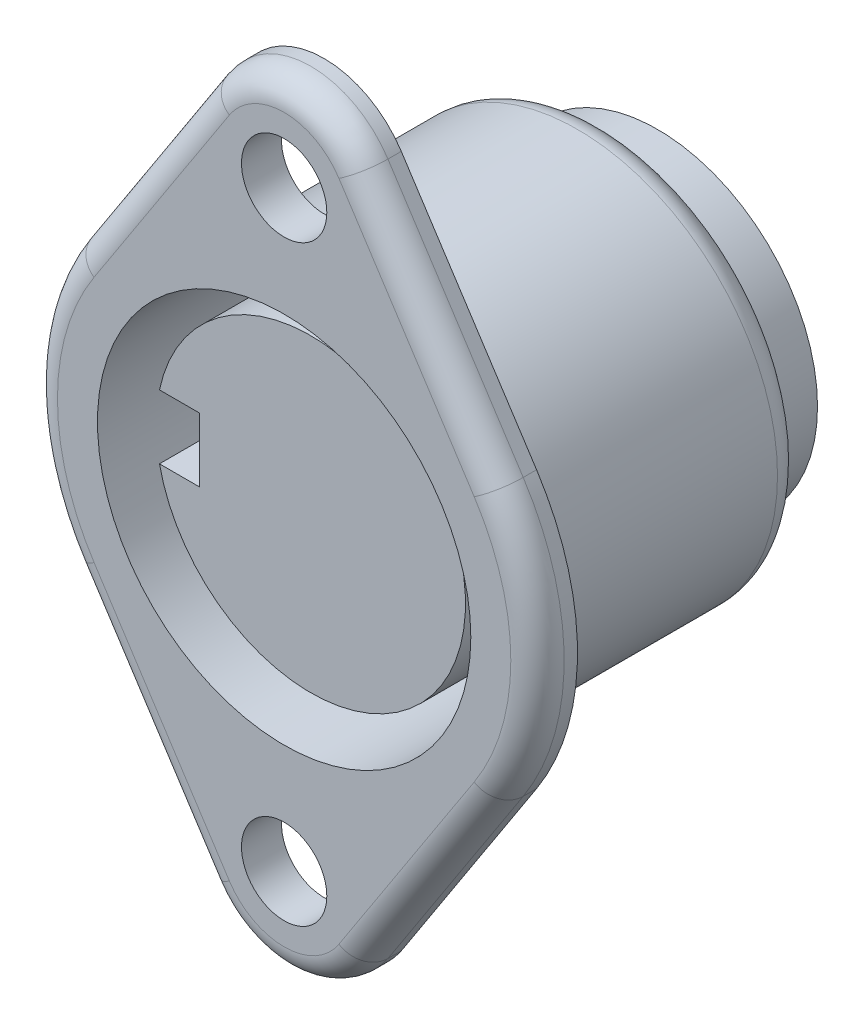
SolidWorks part; units mm, degrees
material "ABS"
ref_plane "Front Plane" through (0, 0, 0) normal (0, 0, 1) x (1, 0, 0)
ref_plane "Top Plane" through (0, 0, 0) normal (0, 1, 0) x (1, 0, 0)
ref_plane "Right Plane" through (0, 0, 0) normal (1, 0, 0) x (0, 0, -1)
sketch "Sketch1" plane through (0, 0, 0) normal (0, 0, 1) x (1, 0, 0)
  circle A0 centre (0, 0) radius 7.5
  dimension "D1" = 15
extrude "Boss-Extrude1" add sketch "Sketch1" along normal blind 10.5
fillet "Fillet1" radius 1 1 edges at (7.5, 0, 0)
sketch "Sketch2" plane through (0, 0, 0) normal (0, 0, -1) x (-1, 0, 0)
  circle A0 centre (0, 0) radius 6
  dimension "D1" = 12
extrude "Boss-Extrude2" add sketch "Sketch2" along normal blind 2
sketch "Sketch3" plane through (0, 0, 10.5) normal (0, 0, 1) x (1, 0, 0)
  line L0 (0, 0) -> (0, 14.55) construction
  line L1 (0, 0) -> (0, -14.55) construction
  line L2 (-9.5, 0) -> (9.5, 0) construction
  line L3 (-7.9649, 5.1779) -> (-2.8925, 12.9804)
  line L4 (7.9649, 5.1779) -> (2.8925, 12.9804)
  line L5 (7.9649, -5.1779) -> (2.8925, -12.9804)
  line L6 (-7.9649, -5.1779) -> (-2.8925, -12.9804)
  circle A0 centre (0, 0) radius 9.5 construction
  circle A1 centre (0, 11.1) radius 3.45 construction
  circle A2 centre (0, -11.1) radius 3.45 construction
  arc A3 (-7.9649, -5.1779) -> (-7.9649, 5.1779) centre (0, 0) cw
  arc A4 (7.9649, -5.1779) -> (7.9649, 5.1779) centre (0, 0) ccw
  arc A5 (-2.8925, -12.9804) -> (2.8925, -12.9804) centre (0, -11.1) ccw
  arc A6 (-2.8925, 12.9804) -> (2.8925, 12.9804) centre (0, 11.1) cw
  circle A7 centre (0, -11.1) radius 1.6
  circle A8 centre (0, 11.1) radius 1.6
  point P7 (0, 11.1)
  point P8 (0, -11.1)
  dimension "D6" = 3.2
  dimension "D1" = 14.55
  dimension "D2" = 29.1
  dimension "D3" = 19
  dimension "D4" = 22.2
  dimension "D5" = 3.45
extrude "Boss-Extrude3" add sketch "Sketch3" along normal blind 1.5
fillet "Fillet2" radius 1 8 edges at (-9.5, 0, 12) (-5.4287, 9.0792, 12) (0, 14.55, 12) (5.4287, 9.0792, 12) (9.5, 0, 12) (5.4287, -9.0792, 12) (0, -14.55, 12) (-5.4287, -9.0792, 12)
sketch "Sketch4" plane through (0, 0, 12) normal (0, 0, 1) x (1, 0, 0)
  circle A0 centre (0, 0) radius 7
  dimension "D1" = 14
extrude "Cut-Extrude1" cut sketch "Sketch4" against normal blind 8.34
sketch "Sketch5" plane through (0, 0, 3.66) normal (0, 0, 1) x (1, 0, 0)
  circle A0 centre (0, 0) radius 5.8
  dimension "D1" = 11.6
extrude "Boss-Extrude4" add sketch "Sketch5" along a picked direction on the side of the normal offset from surface (7.34 mm away) 1
sketch "Sketch6" plane through (0, 0, 11) normal (0, 0, 1) x (1, 0, 0)
  line L0 (0, 0) -> (-8.0806, 0) construction
  line L1 (-5.6745, -1.2) -> (-4.1745, -1.2)
  line L2 (-4.1745, -1.2) -> (-4.1745, 1.2)
  line L3 (-4.1745, 1.2) -> (-5.6745, 1.2)
  circle A0 centre (0, 0) radius 5.8 construction
  circle A1 centre (0, 0) radius 5.8 construction
  arc A2 (-5.6745, -1.2) -> (-5.6745, 1.2) centre (0, 0) cw
  dimension "D1" = 2.4
  dimension "D2" = 1.5
extrude "Cut-Extrude2" cut sketch "Sketch6" against normal up to surface (7.34 mm away) up to face at (7, 0, 3.66)
